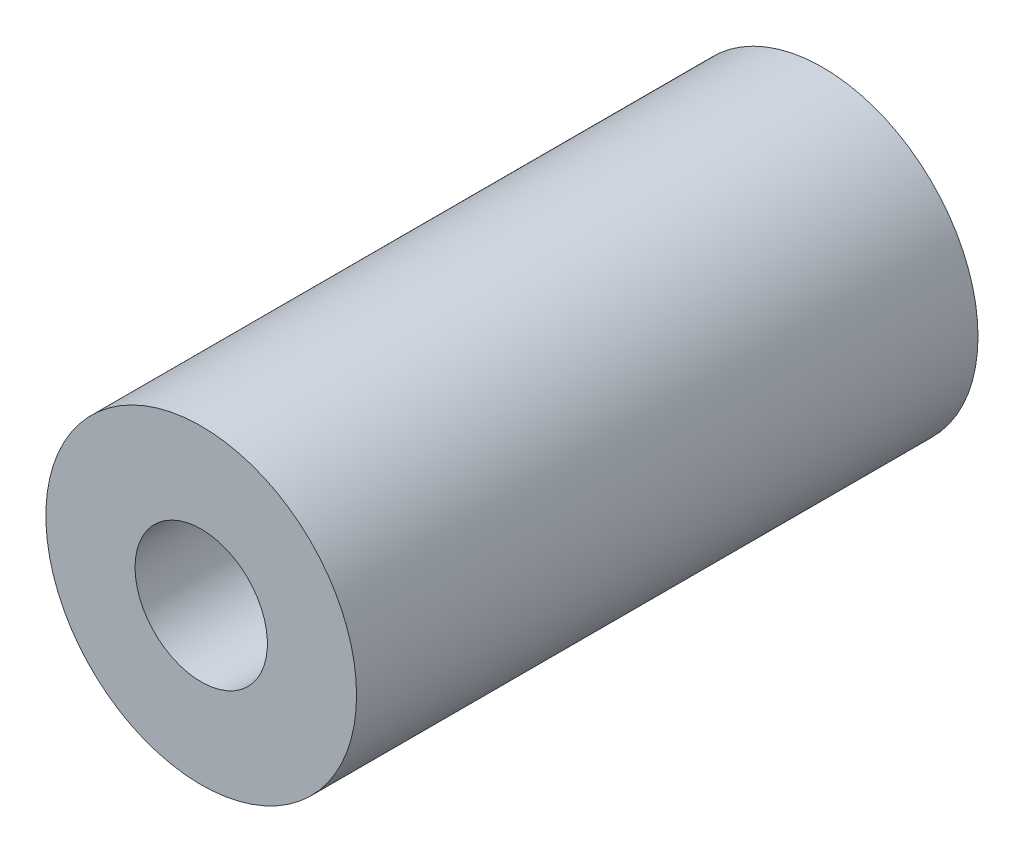
SolidWorks part; units mm, degrees
ref_plane "Front Plane" through (0, 0, 0) normal (0, 0, 1) x (1, 0, 0)
ref_plane "Top Plane" through (0, 0, 0) normal (0, 1, 0) x (1, 0, 0)
ref_plane "Right Plane" through (0, 0, 0) normal (1, 0, 0) x (0, 0, -1)
sketch "Sketch1" plane through (0, 0, 0) normal (0, 0, 1) x (1, 0, 0)
  circle A0 centre (0, 0) radius 3.175
  dimension "D1" = 6.35
extrude "Boss-Extrude1" add sketch "Sketch1" along normal blind 12.7
hole_wizard "#6-32 Tapped Hole1" positions "Sketch3" profile "Sketch2" tap size "#6-32" standard "ANSI Inch" end condition through all
sketch "Sketch3" plane through (0, 0, 0) normal (0, 0, -1) x (-1, 0, 0)
  point P0 (0, 0)
sketch "Sketch2" plane through (0, 0, 0) normal (1, 0, 0) x (0, 1, 0)
  line L0 (0, 0) -> (0, 12.7)
  line L1 (0, 12.7) -> (1.3525, 12.7)
  line L2 (1.3525, 12.7) -> (1.3525, 0)
  line L5 (1.3525, 0) -> (0, 0)
  line L11 (0, -6.35) -> (0, 107.95) construction
  dimension "Thru Tap Drill Dia." = 2.7051
  dimension "Thru Tap Drill Depth" = 12.7
cosmetic thread "Hole Thread1" parameters "D2"=3.5052
